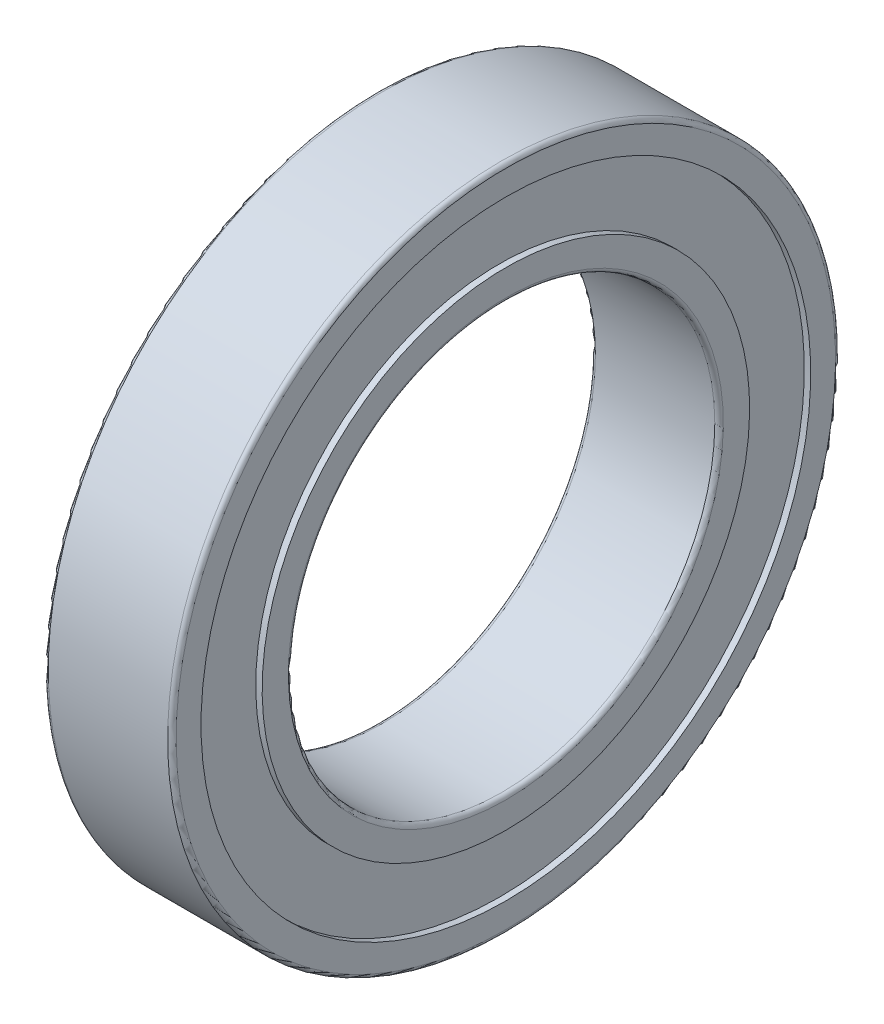
SolidWorks part; units mm, degrees
ref_plane "Front Plane" through (0, 0, 0) normal (0, 0, 1) x (1, 0, 0)
ref_plane "Top Plane" through (0, 0, 0) normal (0, 1, 0) x (1, 0, 0)
ref_plane "Right Plane" through (0, 0, 0) normal (1, 0, 0) x (0, 0, -1)
sketch "Sketch1" plane through (0, 0, 0) normal (0, 0, 1) x (1, 0, 0)
  line L0 (0, 0) -> (9, 0) construction
  line L1 (0, 15) -> (0, 17.15)
  line L2 (0, 17.15) -> (0.45, 17.15)
  line L3 (0.45, 17.15) -> (0.45, 21.45)
  line L4 (0.45, 21.45) -> (0, 21.45)
  line L5 (0, 21.45) -> (0, 23.5)
  line L6 (0, 23.5) -> (9, 23.5)
  line L7 (9, 23.5) -> (9, 21.45)
  line L8 (9, 21.45) -> (8.55, 21.45)
  line L9 (8.55, 21.45) -> (8.55, 17.15)
  line L10 (8.55, 17.15) -> (9, 17.15)
  line L11 (9, 17.15) -> (9, 15)
  line L12 (9, 15) -> (0, 15)
  dimension "D_s" = 30
  dimension "D" = 47
  dimension "B" = 9
  dimension "MSM_3" = 34.3
  dimension "MSM_4" = 42.9
  dimension "MSM_5" = 8.1
revolve "Revolve1" add sketch "Sketch1" angle 360 about L0
fillet "Fillet1" radius 0.3 4 edges at (0, -15, 0) (9, -15, 0) (0, -23.5, 0) (9, -23.5, 0)
